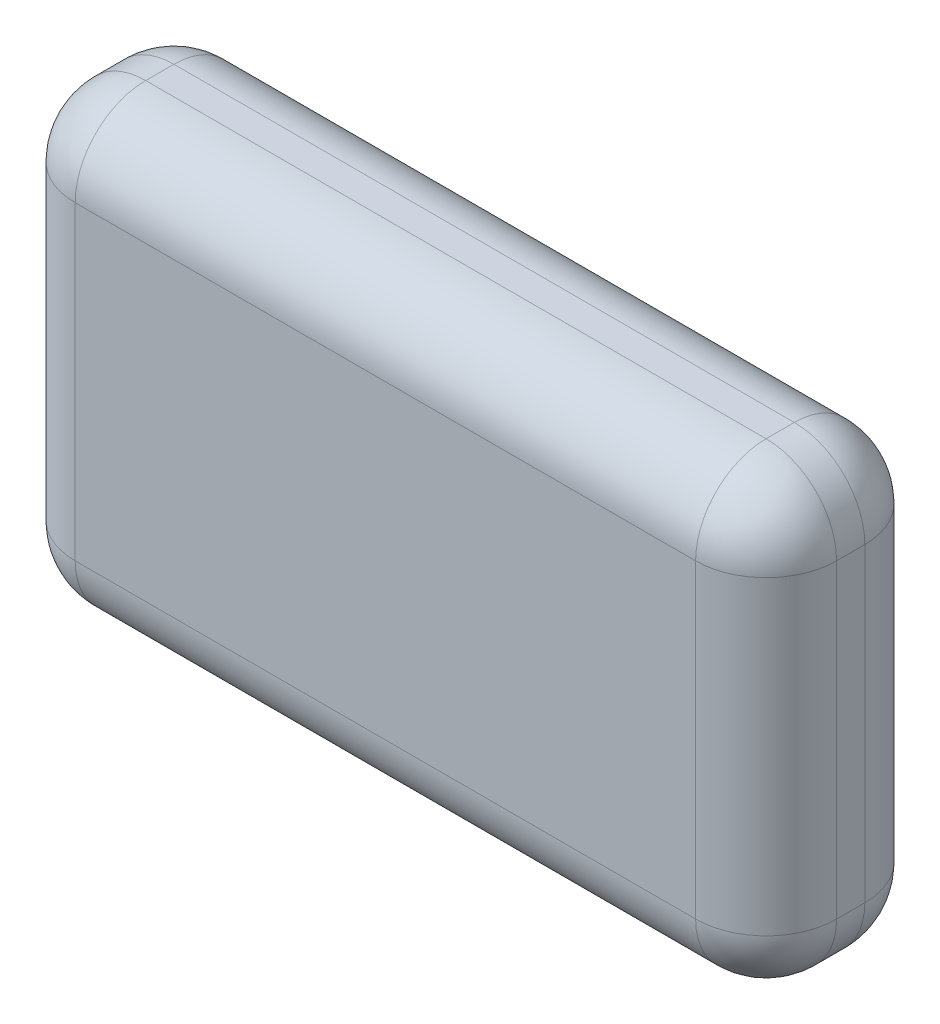
SolidWorks part; units mm, degrees
ref_plane "Alzado" through (0, 0, 0) normal (0, 0, 1) x (1, 0, 0)
ref_plane "Planta" through (0, 0, 0) normal (0, 1, 0) x (1, 0, 0)
ref_plane "Vista lateral" through (0, 0, 0) normal (1, 0, 0) x (0, 0, -1)
sketch "Croquis1" plane through (0, 0, 0) normal (0, 0, 1) x (1, 0, 0)
  line L1 (-54, -32) -> (54, -32)
  line L2 (-54, -32) -> (-54, 32)
  line L3 (-54, 32) -> (54, 32)
  line L4 (54, -32) -> (54, 32)
  line L5 (-54, -32) -> (54, 32) construction
  line L6 (-54, 32) -> (54, -32) construction
  point P0 (0, 0)
  dimension "D1" = 108
  dimension "D2" = 64
extrude "Saliente-Extruir1" add sketch "Croquis1" along normal blind 24
fillet "Redondeo1" radius 10 12 edges at (-54, -32, 12) (0, -32, 24) (0, -32, 0) (54, -32, 12) (54, 0, 24) (54, 0, 0) (54, 32, 12) (0, 32, 24) (-54, 32, 12) (0, 32, 0) (-54, 0, 0) (-54, 0, 24)
